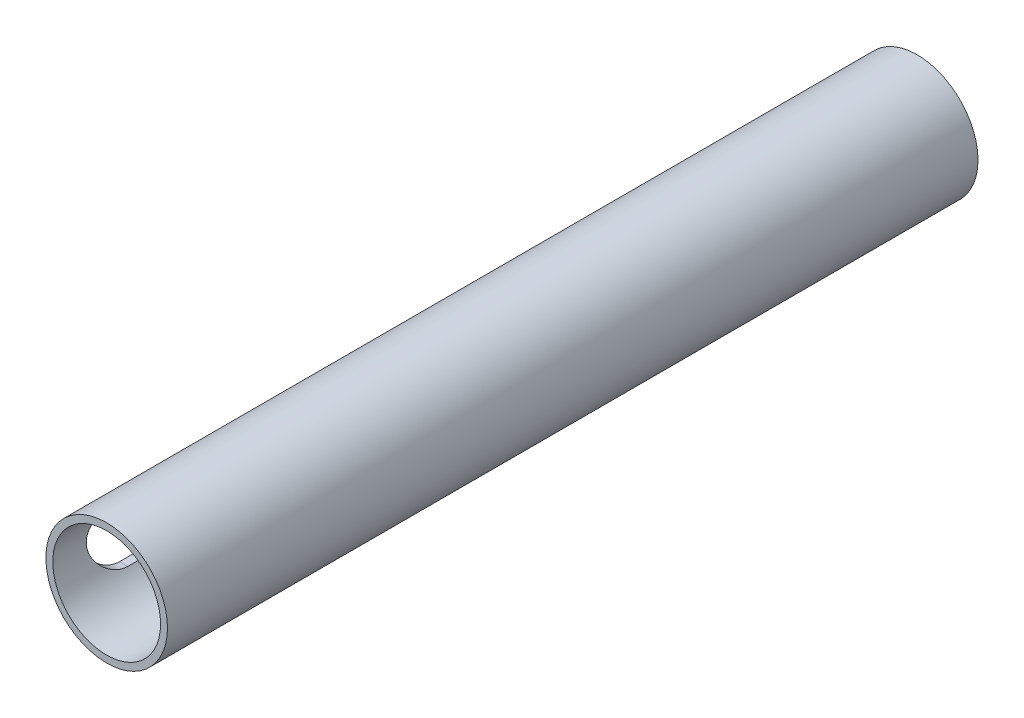
SolidWorks part; units mm, degrees
ref_plane "Front Plane" through (0, 0, 0) normal (0, 0, 1) x (1, 0, 0)
ref_plane "Top Plane" through (0, 0, 0) normal (0, 1, 0) x (1, 0, 0)
ref_plane "Right Plane" through (0, 0, 0) normal (1, 0, 0) x (0, 0, -1)
sketch "Sketch1" plane through (0, 0, 0) normal (0, 0, 1) x (1, 0, 0)
  circle A0 centre (0, 0) radius 11.43
  point P3 (0, 0)
  dimension "D1" = 22.86
extrude "Boss-Extrude1" add sketch "Sketch1" along normal blind 152.4
sketch "Sketch2" plane through (0, 0, 152.4) normal (0, 0, 1) x (1, 0, 0)
  circle A0 centre (0, 0) radius 10.1332
extrude "Cut-Extrude1" cut sketch "Sketch2" against normal blind 149.86
sketch "Sketch3" plane through (0, 0, 0) normal (1, 0, 0) x (0, 0, -1)
  line L0 (-10.671, 0) -> (-140.211, 0) construction
  line L1 (-10.671, -5.9034) -> (-140.211, -5.9034)
  line L2 (-10.671, 5.9034) -> (-140.211, 5.9034)
  arc A0 (-10.671, -5.9034) -> (-10.671, 5.9034) centre (-10.671, 0) ccw
  arc A1 (-140.211, 5.9034) -> (-140.211, -5.9034) centre (-140.211, 0) ccw
  point P2 (-75.441, 0)
  dimension "D1" = 11.8067
  dimension "D2" = 129.54
extrude "Cut-Extrude2" cut sketch "Sketch3" against normal blind 12.7 contours L2 A1 L1 A0
